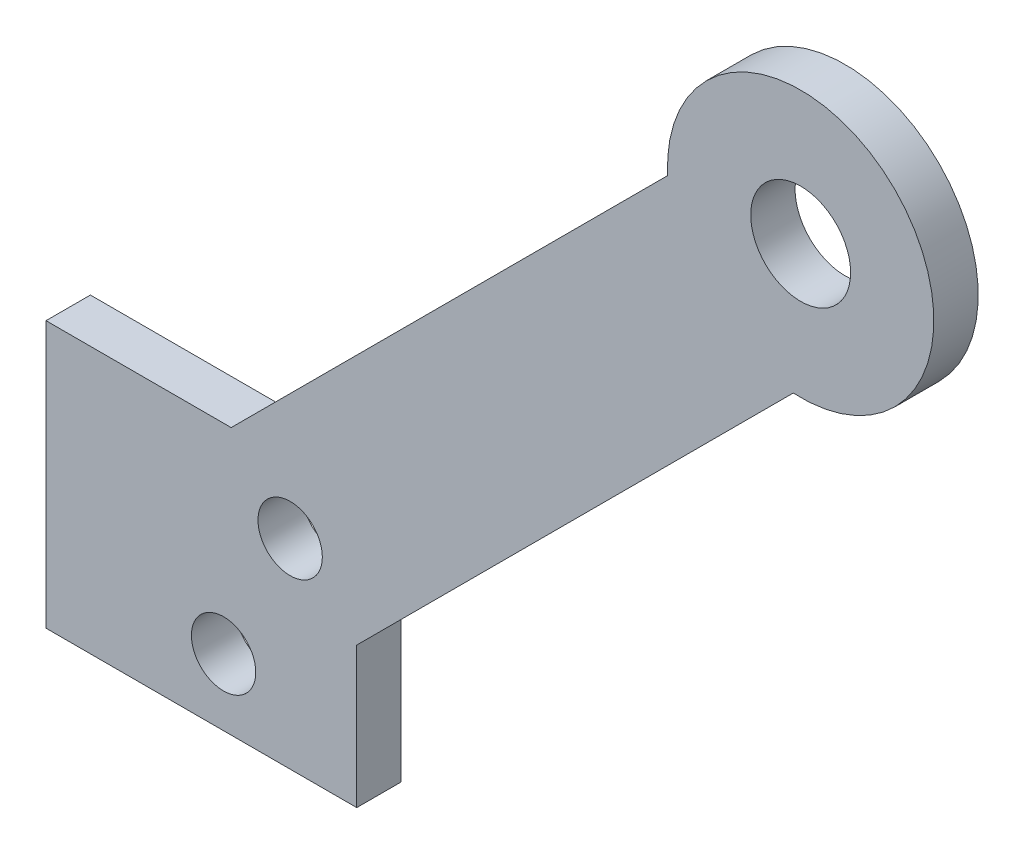
SolidWorks part; units mm, degrees
material "7075-T6 (SN)"
ref_plane "Front Plane" through (0, 0, 0) normal (0, 0, 1) x (1, 0, 0)
ref_plane "Top Plane" through (0, 0, 0) normal (0, 1, 0) x (1, 0, 0)
ref_plane "Right Plane" through (0, 0, 0) normal (1, 0, 0) x (0, 0, -1)
sketch "Sketch1" plane through (0, 0, 0) normal (0, 0, 1) x (1, 0, 0)
  circle A0 centre (50, 50) radius 6
  circle A1 centre (50, 50) radius 2.25
extrude "Follower_Seat_D4p5" add sketch "Sketch1" along normal blind 2
sketch "Sketch2" plane through (0, 0, 0) normal (0, 0, 1) x (1, 0, 0)
  line L0 (21.1716, 26.8284) -> (44.1716, 49.8284)
  line L1 (44.1716, 49.8284) -> (49.8284, 44.1716)
  line L2 (49.8284, 44.1716) -> (26.8284, 21.1716)
  line L3 (26.8284, 21.1716) -> (21.1716, 26.8284)
extrude "Carriage_To_Follower_Bridge" add sketch "Sketch2" along normal blind 2
sketch "Sketch3" plane through (0, 0, 0) normal (0, 0, 1) x (1, 0, 0)
  line L1 (16, 18) -> (30, 18)
  line L2 (16, 18) -> (16, 30)
  line L3 (16, 30) -> (30, 30)
  line L4 (30, 18) -> (30, 30)
extrude "Carriage_Attachment_Pad" add sketch "Sketch3" along normal blind 2
sketch "Sketch4" plane through (0, 0, 2) normal (0, 0, 1) x (1, 0, 0)
  circle A0 centre (21, 21) radius 1.45
  circle A1 centre (27, 27) radius 1.45
sketch "Sketch5" plane through (0, 0, 2) normal (0, 0, 1) x (1, 0, 0)
  circle A0 centre (24, 21) radius 1.45
  circle A1 centre (27, 27) radius 1.45
extrude "Stop_Mount_D2p9_Through" cut sketch "Sketch5" against normal blind 2.01
